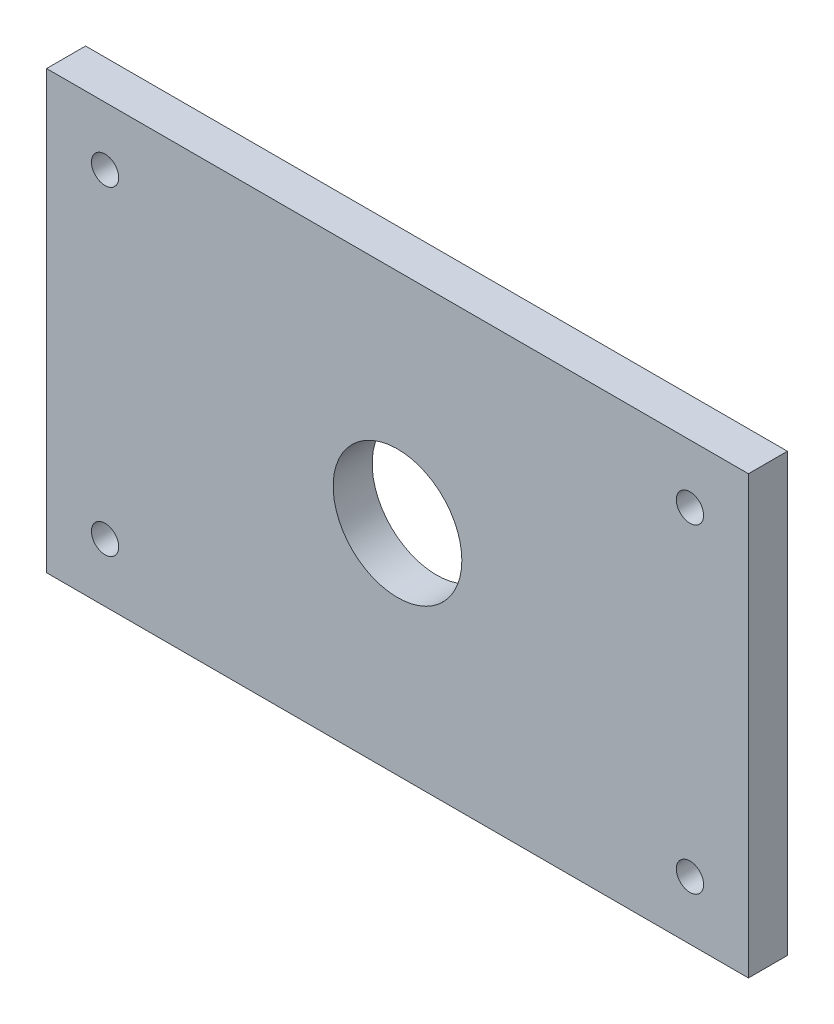
SolidWorks part; units mm, degrees
ref_plane "Front" through (0, 0, 0) normal (0, 0, 1) x (1, 0, 0)
ref_plane "Top" through (0, 0, 0) normal (0, 1, 0) x (1, 0, 0)
ref_plane "Right" through (0, 0, 0) normal (1, 0, 0) x (0, 0, -1)
sketch "ｽｹｯﾁ1" plane through (0, 0, 0) normal (0, 0, 1) x (1, 0, 0)
  line L1 (-45, -28) -> (45, -28)
  line L2 (-45, -28) -> (-45, 28)
  line L3 (-45, 28) -> (45, 28)
  line L4 (45, -28) -> (45, 28)
  line L5 (0, 28) -> (0, -28) construction
  line L6 (-45, 0) -> (45, 0) construction
  circle A0 centre (-37.5, 20.5) radius 1.75
  circle A1 centre (37.5, 20.5) radius 1.75
  circle A2 centre (37.5, -20.5) radius 1.75
  circle A3 centre (-37.5, -20.5) radius 1.75
  point P0 (0, 0)
  dimension "D1" = 75
  dimension "D2" = 75
  dimension "D3" = 3.5
  dimension "D4" = 3.5
  dimension "D5" = 41
  dimension "D6" = 3.5
  dimension "D7" = 3.5
  dimension "D10" = 7.5
  dimension "D11" = 7.5
  dimension "D12" = 7.5
  dimension "D13" = 7.5
  dimension "D14" = 7.5
  dimension "D8" = 56
  dimension "D9" = 90
extrude "ﾎﾞｽ - 押し出し1" add sketch "ｽｹｯﾁ1" along normal blind 5
sketch "ｽｹｯﾁ2" plane through (0, 0, 5) normal (0, 0, 1) x (1, 0, 0)
  circle A0 centre (0, 0) radius 8.25
  dimension "D1" = 16.5
extrude "ｶｯﾄ - 押し出し1" cut sketch "ｽｹｯﾁ2" against normal blind 5
